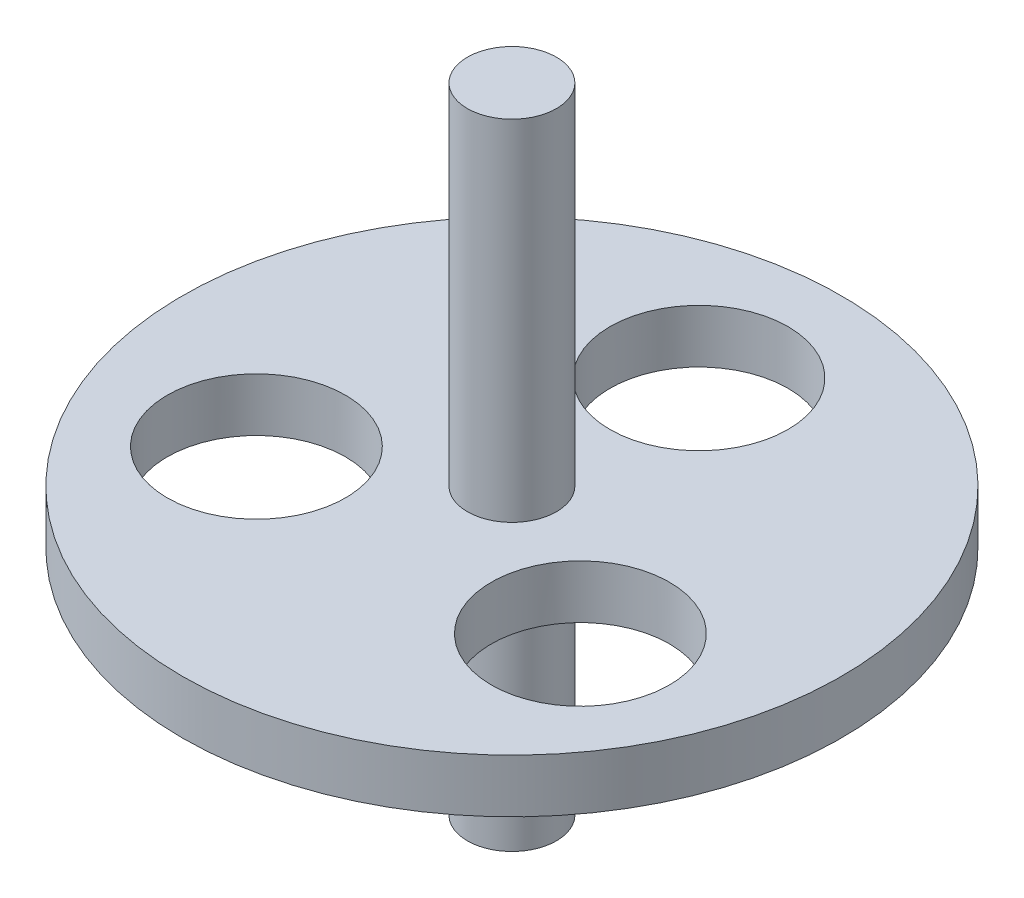
SolidWorks part; units mm, degrees
ref_plane "前视基准面" through (0, 0, 0) normal (0, 0, 1) x (1, 0, 0)
ref_plane "上视基准面" through (0, 0, 0) normal (0, 1, 0) x (1, 0, 0)
ref_plane "右视基准面" through (0, 0, 0) normal (1, 0, 0) x (0, 0, -1)
other "Configuration Table"
sketch "草图1" plane through (0, 0, 0) normal (0, 1, 0) x (1, 0, 0)
  circle A1 centre (0, 0) radius 18.5
  dimension "D1" = 37
extrude "凸台-拉伸1" add sketch "草图1" along normal blind 3
ref_plane "基准面1" through (0, 3, 0) normal (0, 1, 0) x (1, 0, 0)
sketch "草图2" plane through (0, 3, 0) normal (0, 1, 0) x (1, 0, 0)
  circle A0 centre (0, 0) radius 2.5
  dimension "D1" = 5
extrude "凸台-拉伸2" add sketch "草图2" along normal blind 19.6
cosmetic thread "装饰螺纹线2" parameters "D1"=6.6, "D2"=4
ref_plane "基准面2" through (0, 0, 0) normal (0, -1, 0) x (-1, 0, 0)
sketch "草图3" plane through (0, 0, 0) normal (0, -1, 0) x (-1, 0, 0)
  circle A0 centre (0, 0) radius 2.5
  dimension "D1" = 5
extrude "凸台-拉伸3" add sketch "草图3" along normal blind 13
sketch "草图4" plane through (0, 0, 0) normal (0, -1, 0) x (-1, 0, 0)
  line L0 (0, 0) -> (0, 18.5) construction
  line L1 (-6.3864, 10.5) -> (7.5609, 10.5) construction
  circle A0 centre (0, 0) radius 18.5 construction
  circle A1 centre (0, 10.5) radius 5
  dimension "D2" = 10
  dimension "D1" = 10.5
extrude "切除-拉伸1" cut sketch "草图4" against normal up to next
cosmetic thread "装饰螺纹线1" parameters "D2"=11
pattern_circular "阵列(圆周)1" count 3 over 360 about axis through (0, 0, 0) along (0, 1, 0) of "切除-拉伸1"
